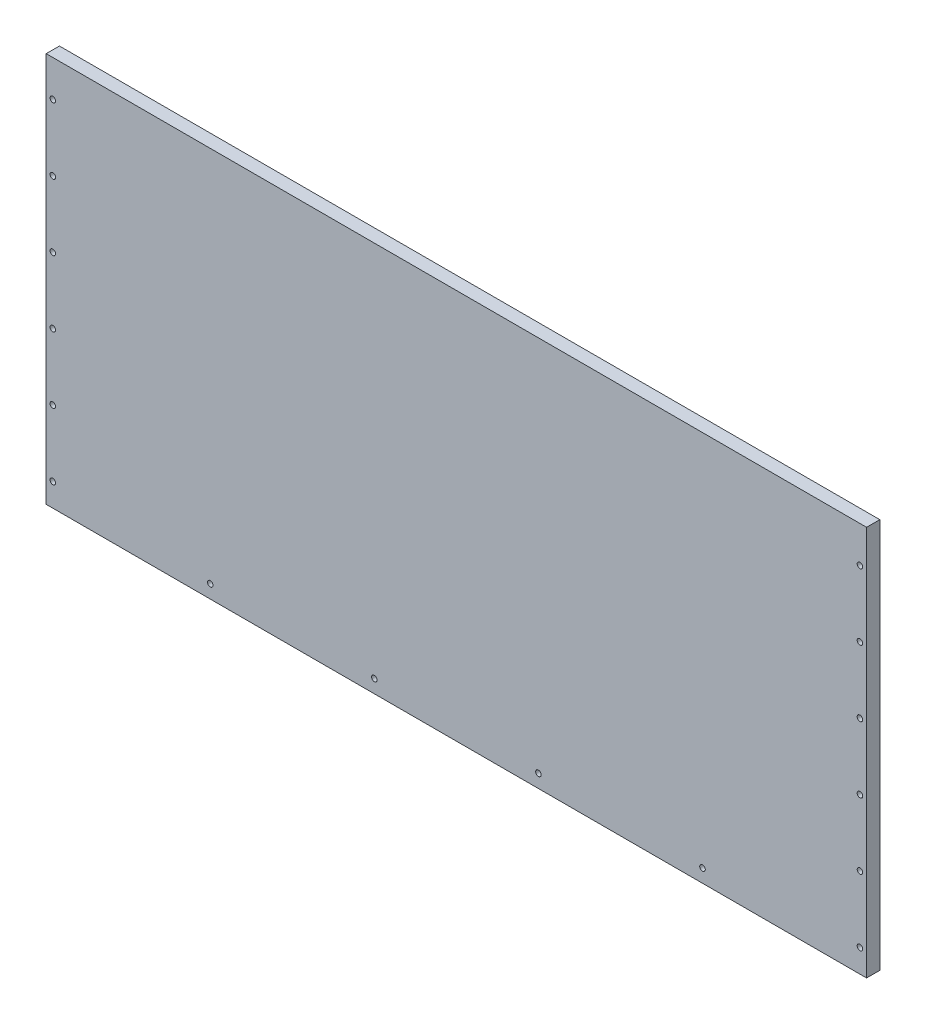
SolidWorks part; units mm, degrees
material "1.4511 (X3CrNb17)"
ref_plane "前视基准面" through (0, 0, 0) normal (0, 0, 1) x (1, 0, 0)
ref_plane "上视基准面" through (0, 0, 0) normal (0, 1, 0) x (1, 0, 0)
ref_plane "右视基准面" through (0, 0, 0) normal (1, 0, 0) x (0, 0, -1)
sketch "草图1" plane through (0, 0, 0) normal (0, 0, 1) x (1, 0, 0)
  line L1 (-310, 147.5) -> (310, 147.5)
  line L2 (-310, 147.5) -> (-310, -147.5)
  line L3 (-310, -147.5) -> (310, -147.5)
  line L4 (310, 147.5) -> (310, -147.5)
  line L5 (-310, 147.5) -> (310, -147.5) construction
  line L6 (-310, -147.5) -> (310, 147.5) construction
  point P1 (0, 0)
  dimension "D1" = 620
  dimension "D2" = 295
extrude "凸台-拉伸1" add sketch "草图1" along normal blind 10
sketch "草图2" plane through (0, 0, 10) normal (0, 0, 1) x (1, 0, 0)
  line L0 (-305, 120) -> (305, 120) construction
  line L1 (310, 147.5) -> (-310, 147.5) construction
  point P3 (0, 120)
  dimension "D1" = 610
  dimension "D2" = 27.5
hole_wizard "M5 螺纹孔1" positions "草图3" profile "草图4" tap size "M5" standard "GB"
sketch "草图3" plane through (0, 0, 10) normal (0, 0, 1) x (1, 0, 0)
  point P0 (-305, 120)
  point P3 (305, 120)
sketch "草图4" plane through (-305, 120, 10) normal (1, 0, 0) x (0, -1, 0)
  line L0 (0, 0) -> (0, 13.4618)
  line L1 (0, 13.4618) -> (2.1, 12.2)
  line L2 (2.1, 12.2) -> (2.1, 0)
  line L5 (2.1, 0) -> (0, 0)
  line L10 (0, 13.4618) -> (-2.1, 12.2) construction
  line L11 (0, -6.35) -> (0, 107.95) construction
  dimension "螺纹孔钻头直径" = 4.2
  dimension "螺纹孔钻头深度" = 12.2
  dimension "导头角度" = 118
cosmetic thread "孔螺蚊线1"
cosmetic thread "孔螺蚊线2"
pattern_linear "阵列(线性)1" count 6 spacing 50 along (0, -1, 0) of "M5 螺纹孔1"
cosmetic thread "孔螺蚊线3"
cosmetic thread "孔螺蚊线4"
cosmetic thread "孔螺蚊线5"
cosmetic thread "孔螺蚊线6"
cosmetic thread "孔螺蚊线7"
cosmetic thread "孔螺蚊线8"
cosmetic thread "孔螺蚊线9"
cosmetic thread "孔螺蚊线10"
cosmetic thread "孔螺蚊线11"
cosmetic thread "孔螺蚊线12"
sketch "草图5" plane through (0, 0, 10) normal (0, 0, 1) x (1, 0, 0)
  line L0 (-310, -147.5) -> (310, -147.5) construction
  line L1 (-310, 147.5) -> (-310, -147.5) construction
  point P0 (-186, -137.5)
  point P5 (-62, -137.5)
  point P7 (62, -137.5)
  point P8 (186, -137.5)
  dimension "D1" = 10
  dimension "D2" = 124
  dimension "D3" = 4
hole_wizard "M5 螺纹孔2" positions "草图6" profile "草图7" tap size "M5" standard "GB" end condition through all
sketch "草图6" plane through (0, 0, 10) normal (0, 0, 1) x (1, 0, 0)
  point P0 (-186, -137.5)
  point P3 (-62, -137.5)
  point P6 (62, -137.5)
  point P9 (186, -137.5)
sketch "草图7" plane through (-186, -137.5, 10) normal (1, 0, 0) x (0, -1, 0)
  line L0 (0, 0) -> (0, 10)
  line L1 (0, 10) -> (2.1, 10)
  line L2 (2.1, 10) -> (2.1, 0)
  line L5 (2.1, 0) -> (0, 0)
  line L11 (0, -6.35) -> (0, 107.95) construction
  dimension "通孔螺纹孔钻头直径" = 4.2
  dimension "通孔螺纹孔钻头深度" = 10
cosmetic thread "孔螺蚊线13"
cosmetic thread "孔螺蚊线14"
cosmetic thread "孔螺蚊线15"
cosmetic thread "孔螺蚊线16"
